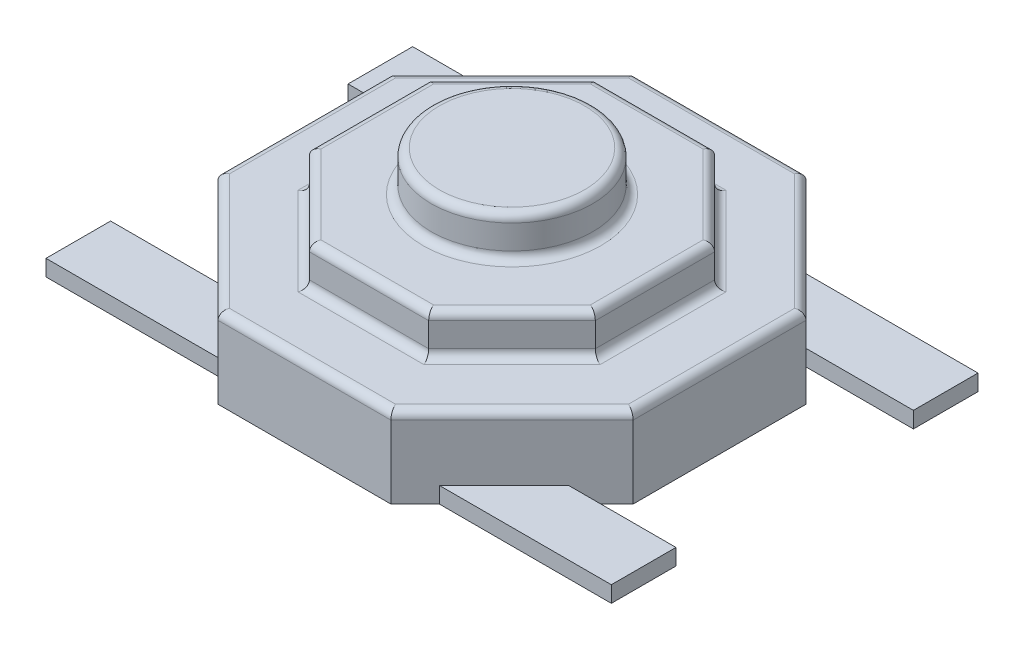
SolidWorks part; units mm, degrees
material "Nickel"
ref_plane "Front Plane" through (0, 0, 0) normal (0, 0, 1) x (1, 0, 0)
ref_plane "Top Plane" through (0, 0, 0) normal (0, 1, 0) x (1, 0, 0)
ref_plane "Right Plane" through (0, 0, 0) normal (1, 0, 0) x (0, 0, -1)
sketch "Sketch1" plane through (0, 0, 0) normal (0, 1, 0) x (1, 0, 0)
  line L0 (-1.07, 2.57) -> (-2.57, 1.07)
  line L1 (1.07, 2.57) -> (-1.07, 2.57)
  line L2 (2.57, 1.07) -> (2.57, -1.07)
  line L3 (1.07, -2.57) -> (-1.07, -2.57)
  line L4 (-2.57, 1.07) -> (-2.57, -1.07)
  line L5 (2.57, 2.57) -> (-2.57, -2.57) construction
  line L6 (2.57, -2.57) -> (-2.57, 2.57) construction
  line L7 (2.57, 1.07) -> (1.07, 2.57)
  line L8 (2.57, -1.07) -> (1.07, -2.57)
  line L9 (-1.07, -2.57) -> (-2.57, -1.07)
  point P0 (0, 0)
  dimension "D1" = 5.14
  dimension "D2" = 5.14
extrude "Boss-Extrude1" add sketch "Sketch1" along normal blind 1
sketch "Sketch2" plane through (0, 1, 0) normal (0, 1, 0) x (1, 0, 0)
  line L16 (-1.77, 0.7386) -> (-1.77, -0.7386)
  line L17 (-1.77, -0.7386) -> (-0.7386, -1.77)
  line L18 (-0.7386, -1.77) -> (0.7386, -1.77)
  line L19 (0.7386, -1.77) -> (1.77, -0.7386)
  line L20 (1.77, -0.7386) -> (1.77, 0.7386)
  line L21 (1.77, 0.7386) -> (0.7386, 1.77)
  line L22 (0.7386, 1.77) -> (-0.7386, 1.77)
  line L23 (-0.7386, 1.77) -> (-1.77, 0.7386)
  line L24 (-1.77, 0.7386) -> (-1.77, -0.7386)
  line L25 (-1.77, -0.7386) -> (-0.7386, -1.77)
  line L26 (-0.7386, -1.77) -> (0.7386, -1.77)
  line L27 (0.7386, -1.77) -> (1.77, -0.7386)
  line L28 (1.77, -0.7386) -> (1.77, 0.7386)
  line L29 (1.77, 0.7386) -> (0.7386, 1.77)
  line L30 (0.7386, 1.77) -> (-0.7386, 1.77)
  line L31 (-0.7386, 1.77) -> (-1.77, 0.7386)
  dimension "D1" = 0.8
extrude "Boss-Extrude2" add sketch "Sketch2" along normal blind 0.5
sketch "Sketch3" plane through (0, 1.5, 0) normal (0, 1, 0) x (1, 0, 0)
  circle A0 centre (0, 0) radius 1
  dimension "D1" = 2
extrude "Boss-Extrude3" add sketch "Sketch3" along normal blind 0.5
fillet "Fillet1" radius 0.1 25 edges at (-1.77, 1, 0) (-1.2543, 1, 1.2543) (0, 1, 1.77) (1.2543, 1, 1.2543) (1.77, 1, 0) (1.2543, 1, -1.2543) (0, 1, -1.77) (-1.2543, 1, -1.2543) (-1.82, 1, -1.82) (0, 1, -2.57) (1.82, 1, -1.82) (2.57, 1, 0) (1.82, 1, 1.82) (0, 1, 2.57) (-1.82, 1, 1.82) (-2.57, 1, 0) (0, 1.5, -1.77) (1.2543, 1.5, -1.2543) (1.77, 1.5, 0) (1.2543, 1.5, 1.2543) (0, 1.5, 1.77) (-1.2543, 1.5, 1.2543) (-1.77, 1.5, 0) (-1.2543, 1.5, -1.2543) (0, 1.5, 1)
sketch "Sketch4" plane through (0, 0, 0) normal (0, -1, 0) x (1, 0, 0)
  line L0 (0.7801, 1.87) -> (-0.7801, 1.87) construction
  line L1 (-3.5, 1.47) -> (3.5, 1.47)
  line L2 (-3.5, 1.47) -> (-3.5, 2.27)
  line L3 (-3.5, 2.27) -> (3.5, 2.27)
  line L4 (3.5, 1.47) -> (3.5, 2.27)
  line L5 (-3.5, 1.47) -> (3.5, 2.27) construction
  line L6 (-3.5, 2.27) -> (3.5, 1.47) construction
  line L7 (1.1, 0) -> (-1.1, 0) construction
  line L8 (-3.5, -2.27) -> (3.5, -1.47) construction
  line L9 (-3.5, -1.47) -> (3.5, -2.27) construction
  line L10 (3.5, -1.47) -> (3.5, -2.27)
  line L11 (-3.5, -2.27) -> (3.5, -2.27)
  line L12 (-3.5, -1.47) -> (-3.5, -2.27)
  line L13 (-3.5, -1.47) -> (3.5, -1.47)
  point P0 (0, 1.87)
  point P13 (0, -1.87)
  dimension "D1" = 7
  dimension "D2" = 0.8
extrude "Boss-Extrude4" add sketch "Sketch4" against normal blind 0.2
fillet "Fillet2" radius 0.1 1 edges at (0, 2, 1)
